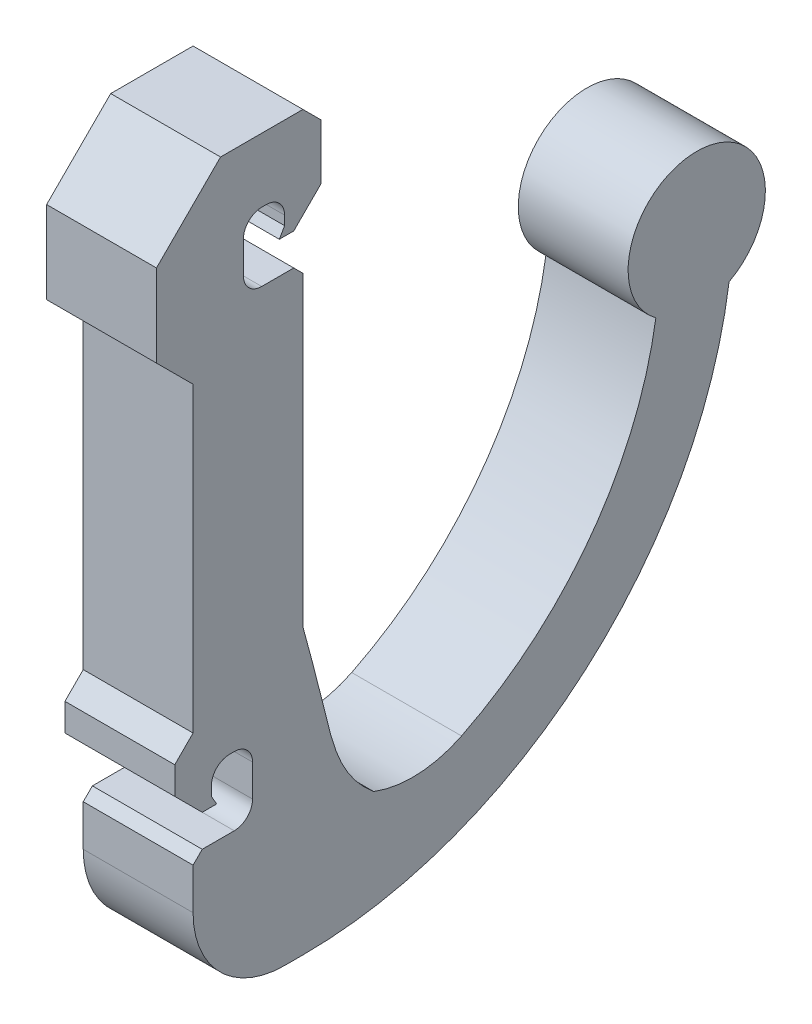
SolidWorks part; units mm, degrees
ref_plane "Front Plane" through (0, 0, 0) normal (0, 0, 1) x (1, 0, 0)
ref_plane "Top Plane" through (0, 0, 0) normal (0, 1, 0) x (1, 0, 0)
ref_plane "Right Plane" through (0, 0, 0) normal (1, 0, 0) x (0, 0, -1)
sketch "Sketch2" plane through (0, 0, 0) normal (1, 0, 0) x (0, 0, -1)
  line L1 (-6, 40) -> (6, 40)
  line L2 (-6, 40) -> (-6, -40)
  line L3 (-6, -40) -> (6, -40)
  line L4 (6, 40) -> (6, -32)
  arc A0 (52.5577, 0.4093) -> (44.5577, 1.0014) centre (49.0254, 7.0254) ccw
  arc A2 (6, -32) -> (44.5577, 1.0014) centre (6, 7.0254) ccw
  arc A3 (6, -40) -> (52.5577, 0.4093) centre (6, 7.0254) ccw
  point P0 (0, 0)
  dimension "D3" = 15
  dimension "D1" = 80
  dimension "D2" = 12
extrude "Boss-Extrude1" add sketch "Sketch2" along normal blind 12
fillet "Fillet1" radius 12 1 edges at (6, -32, -6)
fillet "Fillet2" radius 10 1 edges at (6, -40, 6)
sketch "Sketch3" plane through (12, 0, 0) normal (1, 0, 0) x (0, 0, -1)
  line L0 (-6, 40) -> (-6, -30) construction
  line L1 (-6, -20) -> (-4, -20)
  line L2 (-6, -20) -> (-6, -24.5)
  line L3 (-6, -24.5) -> (0.5, -24.5)
  line L4 (0.5, -20) -> (0.5, -24.5)
  line L5 (6, -17.1897) -> (6, 40) construction
  line L6 (6, 30) -> (4, 30)
  line L7 (6, 30) -> (6, 25.5)
  line L8 (6, 25.5) -> (-0.5, 25.5)
  line L9 (-0.5, 30) -> (-0.5, 25.5)
  line L10 (6, 40) -> (-6, 40) construction
  line L13 (-0.5, 30) -> (-0.5, 33)
  line L14 (-0.5, 33) -> (4, 33)
  line L15 (4, 30) -> (4, 33)
  line L17 (0.5, -20) -> (0.5, -17)
  line L18 (0.5, -17) -> (-4, -17)
  line L19 (-4, -20) -> (-4, -17)
  dimension "D1" = 4.5
  dimension "D2" = 4.5
  dimension "D3" = 45.5
  dimension "D4" = 10
  dimension "D5" = 6.5
  dimension "D6" = 6.5
  dimension "D7" = 4.5
  dimension "D8" = 3
  dimension "D9" = 4.5
  dimension "D10" = 3
extrude "Cut-Extrude1" cut sketch "Sketch3" against normal blind 12
chamfer "Chamfer1" distance 3 angle 45 1 edges at (6, 40, 6)
fillet "Fillet3" radius 2 6 edges at (6, -17, -0.5) (6, -17, 4) (6, -24.5, -0.5) (6, 33, -4) (6, 33, 0.5) (6, 25.5, 0.5)
sketch "Sketch4" plane through (12, 0, 0) normal (1, 0, 0) x (0, 0, -1)
  line L0 (6, 30) -> (8, 32)
  line L1 (8, 32) -> (8, 38)
  line L2 (8, 38) -> (6, 40)
  line L3 (6, 40) -> (6, 30)
  line L4 (-6, -20) -> (-8, -18)
  line L5 (-8, -18) -> (-8, -15)
  line L6 (-8, -15) -> (-6, -13)
  line L7 (-6, 37) -> (-6, -20) construction
  line L8 (-6, -13) -> (-6, -20)
  line L9 (-6, 37) -> (-10, 33)
  line L10 (-10, 33) -> (-10, 24)
  line L11 (-10, 24) -> (-6, 20)
  line L12 (-6, 20) -> (-6, 37)
  line L13 (6, -17.1897) -> (6, 25.5) construction
  line L14 (6, -8.9698) -> (8.3922, -17.7033) construction
  line L15 (8.3922, -17.7033) -> (9.0413, -20.6761) construction
  line L16 (9.0413, -20.6761) -> (9.2247, -24.6305) construction
  line L17 (9.2247, -24.6305) -> (13.7332, -28.4055) construction
  line L18 (6, -8.9698) -> (3.756, -12.2895)
  line L19 (3.756, -12.2895) -> (6, -29.5868)
  line L20 (6, -29.5868) -> (13.7332, -28.4055)
  arc A3 (6, -17.1897) -> (23.3283, -27.9419) centre (18, -17.1897) ccw construction
  spline S0 degree 4 poles (6, -8.9698) (8.3922, -17.7033) (9.0413, -20.6761) (9.2247, -24.6305) (13.7332, -28.4055) knots 0 0 0 0 0 1 1 1 1 1
  dimension "D1" = 45
  dimension "D2" = 2
  dimension "D3" = 45
  dimension "D4" = 2
  dimension "D5" = 45
  dimension "D6" = 3
  dimension "D7" = 4
  dimension "D8" = 45
  dimension "D9" = 9
extrude "Boss-Extrude2" add sketch "Sketch4" against normal blind 12
sketch "Sketch5" plane through (12, 0, 0) normal (1, 0, 0) x (0, 0, -1)
  line L0 (6, 30) -> (5, 29)
  line L1 (5, 29) -> (4, 29)
  line L2 (6, 30) -> (8, 32) construction
  line L3 (4, 30) -> (6, 30)
  line L4 (4, 30) -> (3.4226, 29)
  line L5 (3.4226, 29) -> (4, 29)
  line L6 (-6, -20) -> (-5, -21)
  line L7 (-5, -21) -> (-4, -21)
  line L9 (-4, -20) -> (-6, -20)
  line L10 (-8, -18) -> (-6, -20) construction
  line L11 (-4, -20) -> (-3.4226, -21)
  line L12 (-3.4226, -21) -> (-4, -21)
  dimension "D1" = 1
  dimension "D2" = 180
  dimension "D3" = 1
  dimension "D4" = 180
extrude "Boss-Extrude3" add sketch "Sketch5" against normal blind 12
chamfer "Chamfer2" distance 1 angle 45 2 edges at (6, -24.5, 6) (6, 25.5, -6)
